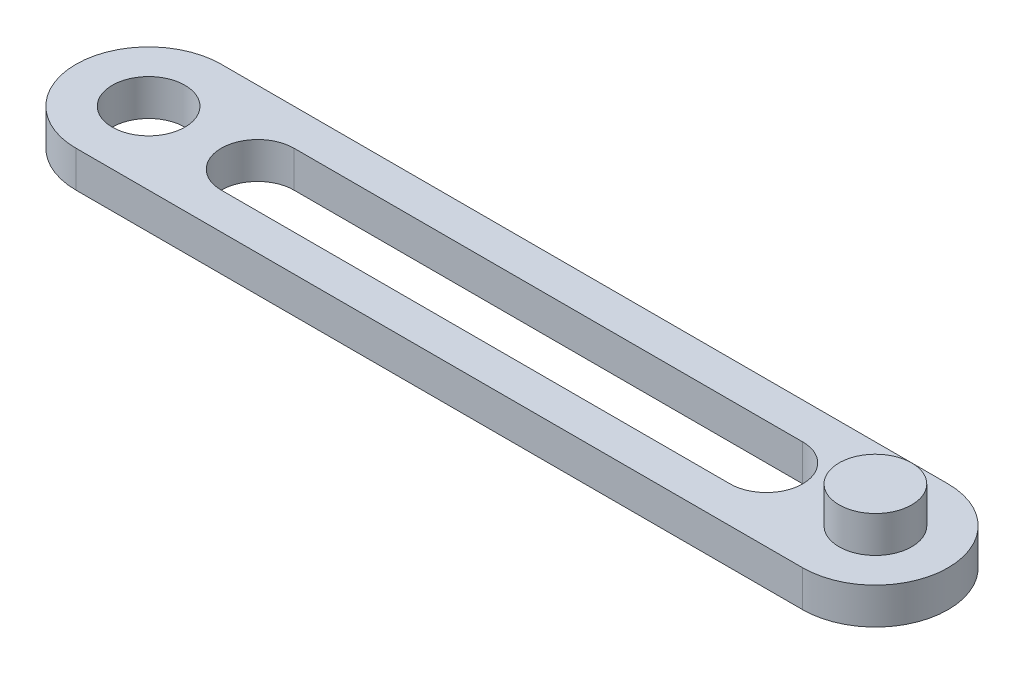
SolidWorks part; units mm, degrees
ref_plane "Front Plane" through (0, 0, 0) normal (0, 0, 1) x (1, 0, 0)
ref_plane "Top Plane" through (0, 0, 0) normal (0, 1, 0) x (1, 0, 0)
ref_plane "Right Plane" through (0, 0, 0) normal (1, 0, 0) x (0, 0, -1)
sketch "Sketch1" plane through (0, 0, 0) normal (0, 1, 0) x (1, 0, 0)
  line L2 (-50, 10) -> (50, 10)
  line L3 (-50, -10) -> (50, -10)
  arc A0 (-50, 10) -> (-50, -10) centre (-50, 0) ccw
  arc A1 (50, -10) -> (50, 10) centre (50, 0) ccw
extrude "Boss-Extrude1" add sketch "Sketch1" along normal blind 5
sketch "Sketch2" plane through (0, 5, 0) normal (0, 1, 0) x (1, 0, 0)
  line L2 (-35, 5) -> (35, 5)
  line L3 (-35, -5) -> (35, -5)
  arc A2 (-35, 5) -> (-35, -5) centre (-35, 0) ccw
  arc A3 (35, -5) -> (35, 5) centre (35, 0) ccw
extrude "Cut-Extrude1" cut sketch "Sketch2" against normal through all
sketch "Sketch3" plane through (0, 5, 0) normal (0, 1, 0) x (1, 0, 0)
  circle A0 centre (50, 0) radius 5
extrude "Boss-Extrude2" add sketch "Sketch3" along normal blind 5 contours A0
sketch "Sketch4" plane through (0, 5, 0) normal (0, 1, 0) x (1, 0, 0)
  circle A0 centre (-50, 0) radius 5
extrude "Cut-Extrude2" cut sketch "Sketch4" against normal through all
